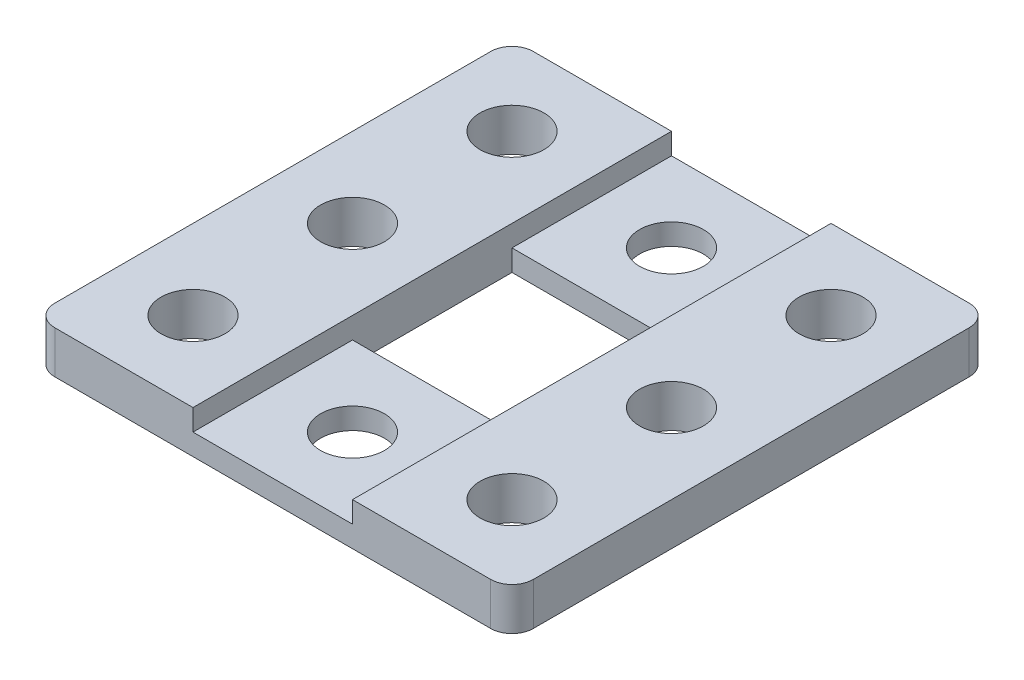
SolidWorks part; units mm, degrees
ref_plane "Front Plane" through (0, 0, 0) normal (0, 0, 1) x (1, 0, 0)
ref_plane "Top Plane" through (0, 0, 0) normal (0, 1, 0) x (1, 0, 0)
ref_plane "Right Plane" through (0, 0, 0) normal (1, 0, 0) x (0, 0, -1)
sketch "Sketch1" plane through (0, 0, 0) normal (0, 1, 0) x (1, 0, 0)
  line L1 (-11.25, 11.25) -> (11.25, 11.25)
  line L2 (-11.25, 11.25) -> (-11.25, -11.25)
  line L3 (-11.25, -11.25) -> (11.25, -11.25)
  line L4 (11.25, 11.25) -> (11.25, -11.25)
  line L5 (-11.25, 11.25) -> (11.25, -11.25) construction
  line L6 (-11.25, -11.25) -> (11.25, 11.25) construction
  point P0 (0, 0)
  dimension "D1" = 22.5
  dimension "D2" = 22.5
extrude "Boss-Extrude1" add sketch "Sketch1" along normal blind 2
sketch "Sketch2" plane through (0, 2, 0) normal (0, 1, 0) x (1, 0, 0)
  line L0 (0, 0) -> (0, 11.25) construction
  line L1 (11.25, 11.25) -> (-11.25, 11.25) construction
  line L2 (0, 11.25) -> (0, -11.25) construction
  line L3 (-11.25, -11.25) -> (11.25, -11.25) construction
  line L4 (-3.75, 11.25) -> (-3.75, -11.25) construction
  line L5 (3.75, 11.25) -> (3.75, -11.25) construction
  line L7 (-3.75, 11.25) -> (3.75, 11.25)
  line L8 (-3.75, 11.25) -> (-3.75, -11.25)
  line L9 (-3.75, -11.25) -> (3.75, -11.25)
  line L10 (3.75, 11.25) -> (3.75, -11.25)
  dimension "D1" = 3.75
  dimension "D2" = 3.75
extrude "Cut-Extrude1" cut sketch "Sketch2" against normal blind 1
sketch "Sketch4" plane through (0, 1, 0) normal (0, 1, 0) x (1, 0, 0)
  line L0 (0, 0) -> (0, 11.25) construction
  line L1 (3.75, 11.25) -> (-3.75, 11.25) construction
  line L2 (0, 11.25) -> (0, -11.25) construction
  line L3 (-3.75, -11.25) -> (3.75, -11.25) construction
  line L4 (0, 3.75) -> (3.75, 3.75) construction
  line L5 (3.75, -11.25) -> (3.75, 11.25) construction
  line L6 (3.75, 3.75) -> (-3.75, 3.75) construction
  line L7 (-3.75, 11.25) -> (-3.75, -11.25) construction
  line L8 (0, 0) -> (-3.75, 0) construction
  line L9 (-3.75, 0) -> (3.75, 0) construction
  line L10 (-3.75, -3.75) -> (0, -3.75) construction
  line L11 (0, -3.75) -> (3.75, -3.75) construction
  line L12 (-2.039, 3.75) -> (-2.039, 11.25) construction
  line L13 (-3.75, 7.5) -> (3.75, 7.5) construction
  line L14 (-3.75, -7.5) -> (3.75, -7.5) construction
  circle A0 centre (0, 7.5) radius 1.5
  circle A1 centre (0, -7.5) radius 1.5
  dimension "D3" = 3.75
  dimension "D1" = 3.75
  dimension "D2" = 3.75
extrude "Cut-Extrude2" cut sketch "Sketch4" against normal blind 2
sketch "Sketch5" plane through (0, 1, 0) normal (0, 1, 0) x (1, 0, 0)
  line L0 (0, 0) -> (-3.75, 0) construction
  line L1 (-3.75, 11.25) -> (-3.75, -11.25) construction
  line L2 (-3.75, 0) -> (3.75, 0) construction
  line L3 (3.75, -11.25) -> (3.75, 11.25) construction
  line L5 (-3.75, 3.75) -> (3.75, 3.75)
  line L6 (-3.75, 3.75) -> (-3.75, -3.75)
  line L7 (-3.75, -3.75) -> (3.75, -3.75)
  line L8 (3.75, 3.75) -> (3.75, -3.75)
  dimension "D1" = 3.75
  dimension "D2" = 3.75
extrude "Cut-Extrude3" cut sketch "Sketch5" against normal blind 2
sketch "Sketch6" plane through (0, 2, 0) normal (0, 1, 0) x (1, 0, 0)
  line L0 (-7.5, 11.25) -> (-7.5, -11.25) construction
  line L1 (-3.75, 11.25) -> (-11.25, 11.25) construction
  line L2 (-11.25, -11.25) -> (-3.75, -11.25) construction
  line L3 (-11.25, 3.75) -> (-3.75, 3.75) construction
  line L4 (-11.25, 11.25) -> (-11.25, -11.25) construction
  line L5 (-3.75, 11.25) -> (-3.75, -11.25) construction
  line L6 (-11.25, -3.75) -> (-3.75, -3.75) construction
  line L7 (-9.2725, 11.25) -> (-9.2725, 3.75) construction
  line L8 (-9.5516, -3.75) -> (-9.5516, -11.25) construction
  circle A0 centre (-7.5, 7.5) radius 1.5
  circle A1 centre (-7.5, -7.5) radius 1.5
  circle A2 centre (-7.5, 0) radius 1.5
  dimension "D1" = 7.5
  dimension "D2" = 7.5
extrude "Cut-Extrude4" cut sketch "Sketch6" against normal blind 2
sketch "Sketch7" plane through (0, 2, 0) normal (0, 1, 0) x (1, 0, 0)
  line L0 (7.5, 11.25) -> (7.5, -11.25) construction
  line L1 (11.25, 11.25) -> (3.75, 11.25) construction
  line L2 (3.75, -11.25) -> (11.25, -11.25) construction
  line L3 (3.75, 0) -> (11.25, 0) construction
  line L4 (3.75, -11.25) -> (3.75, 11.25) construction
  line L5 (11.25, -11.25) -> (11.25, 11.25) construction
  line L6 (3.75, 3.75) -> (11.25, 3.75) construction
  line L7 (3.75, -3.75) -> (11.25, -3.75) construction
  line L8 (5.4404, 11.25) -> (5.4404, 3.75) construction
  line L9 (5.4404, -3.75) -> (5.4404, -11.25) construction
  line L10 (3.75, -7.5) -> (11.25, -7.5) construction
  circle A0 centre (7.5, 0) radius 1.5
  circle A1 centre (7.5, 7.5) radius 1.5
  circle A2 centre (7.5, -7.5) radius 1.5
  dimension "D1" = 7.5
  dimension "D2" = 7.5
extrude "Cut-Extrude5" cut sketch "Sketch7" against normal blind 2
fillet "Fillet1" radius 1 4 edges at (-11.25, 1, -11.25) (-11.25, 1, 11.25) (11.25, 1, 11.25) (11.25, 1, -11.25)
